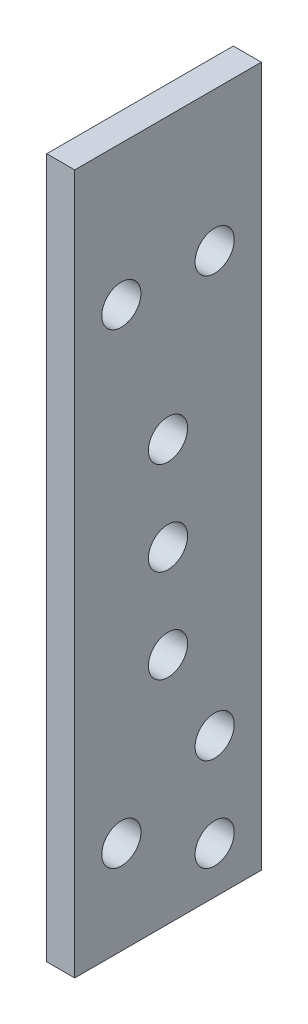
SolidWorks part; units mm, degrees
ref_plane "前视基准面" through (0, 0, 0) normal (0, 0, 1) x (1, 0, 0)
ref_plane "上视基准面" through (0, 0, 0) normal (0, 1, 0) x (1, 0, 0)
ref_plane "右视基准面" through (0, 0, 0) normal (1, 0, 0) x (0, 0, -1)
ref_plane "基准面4" through (36, 0, 0) normal (-1, 0, 0) x (0, -1, 0)
sketch "草图1" plane through (36, 0, 0) normal (-1, 0, 0) x (0, -1, 0)
  line L0 (5, 20) -> (5, 0)
  line L1 (5, 0) -> (80, 0)
  line L2 (80, 0) -> (80, 20)
  line L3 (80, 20) -> (5, 20)
  circle A0 centre (20, 15) radius 2.1
  circle A1 centre (55, 10) radius 2.1
  circle A2 centre (45, 10) radius 2.1
  circle A3 centre (35, 10) radius 2.1
  circle A4 centre (20, 5) radius 2.1
  circle A5 centre (75, 5) radius 2.1
  circle A6 centre (70, 15) radius 2.1
  circle A7 centre (65, 5) radius 2.1
extrude "凸台-拉伸1" add sketch "草图1" against normal blind 3
